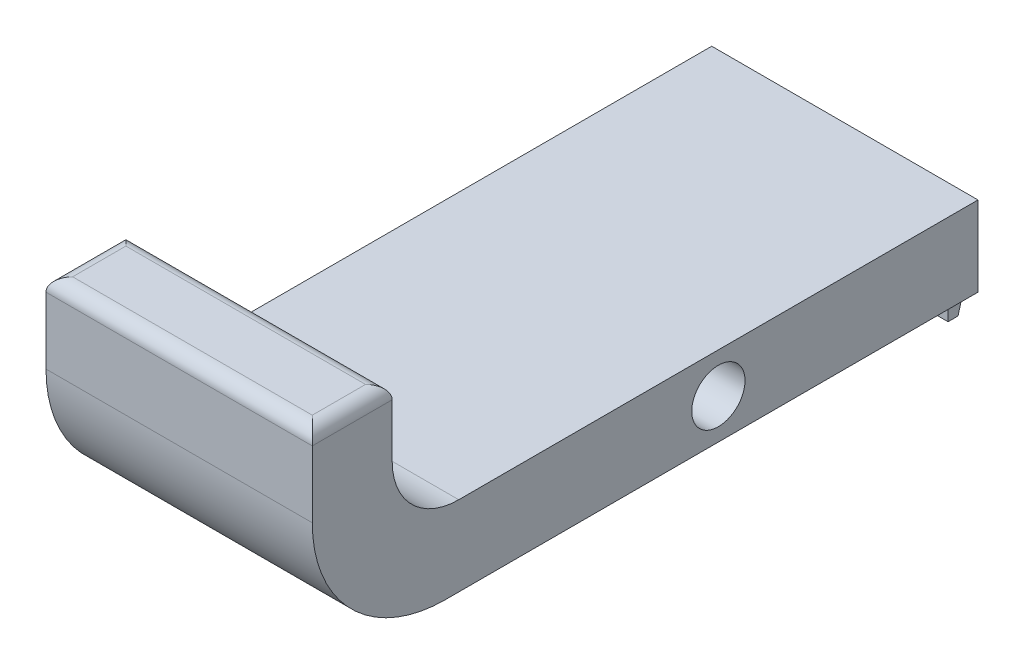
SolidWorks part; units mm, degrees
ref_plane "Front Plane" through (0, 0, 0) normal (0, 0, 1) x (1, 0, 0)
ref_plane "Top Plane" through (0, 0, 0) normal (0, 1, 0) x (1, 0, 0)
ref_plane "Right Plane" through (0, 0, 0) normal (1, 0, 0) x (0, 0, -1)
sketch "Sketch2" plane through (0, 0, 0) normal (0, 0, 1) x (1, 0, 0)
  line L1 (-10, 3) -> (10, 3)
  line L2 (-10, 3) -> (-10, -3)
  line L3 (-10, -3) -> (10, -3)
  line L4 (10, 3) -> (10, -3)
  line L5 (-10, 3) -> (10, -3) construction
  line L6 (-10, -3) -> (10, 3) construction
  point P0 (0, 0)
  dimension "D1" = 20
  dimension "D2" = 6
extrude "Boss-Extrude1" add sketch "Sketch2" along normal blind 50 contours L2 L1 L4 L3
sketch "Sketch5" plane through (0, 0, 0) normal (1, 0, 0) x (0, 0, -1)
  line L0 (0, -3) -> (-0.5, -4.8)
  line L1 (-0.5, -4.8) -> (-1.25, -4.8)
  line L2 (-1.25, -4.8) -> (-1.25, -3)
  line L3 (-50, -3) -> (0, -3) construction
  line L4 (-1.25, -3) -> (0, -3)
  dimension "D1" = 1.8
  dimension "D2" = 0.75
  dimension "D3" = 1.25
extrude "Boss-Extrude3" add sketch "Sketch5" along normal blind 9 and the other way blind 9
sketch "Sketch6" plane through (10, 0, 0) normal (1, 0, 0) x (0, 0, -1)
  line L0 (-19.5, 0) -> (0, 0) construction
  circle A0 centre (-19.5, 0) radius 2
  dimension "D1" = 4
  dimension "D2" = 19.5
extrude "Cut-Extrude1" cut sketch "Sketch6" against normal up to surface (20 mm away) up to face at (-10, 0, 25)
sketch "Sketch7" plane through (0, 3, 0) normal (0, 1, 0) x (1, 0, 0)
  line L0 (10, -50) -> (10, 0) construction
  line L1 (-10, -50) -> (10, -50)
  line L2 (-10, -50) -> (-10, -44)
  line L3 (-10, -44) -> (10, -44)
  line L4 (10, -50) -> (10, -44)
  dimension "D1" = 6
extrude "Boss-Extrude4" add sketch "Sketch7" along normal blind 10
fillet "Fillet1" radius 10 1 edges at (0, -3, 50)
fillet "Fillet2" radius 5 1 edges at (0, 3, 44)
fillet "Fillet3" radius 1 4 edges at (0, 13, 50) (-10, 13, 47) (0, 13, 44) (10, 13, 47)
equation "\"d\"=5"
